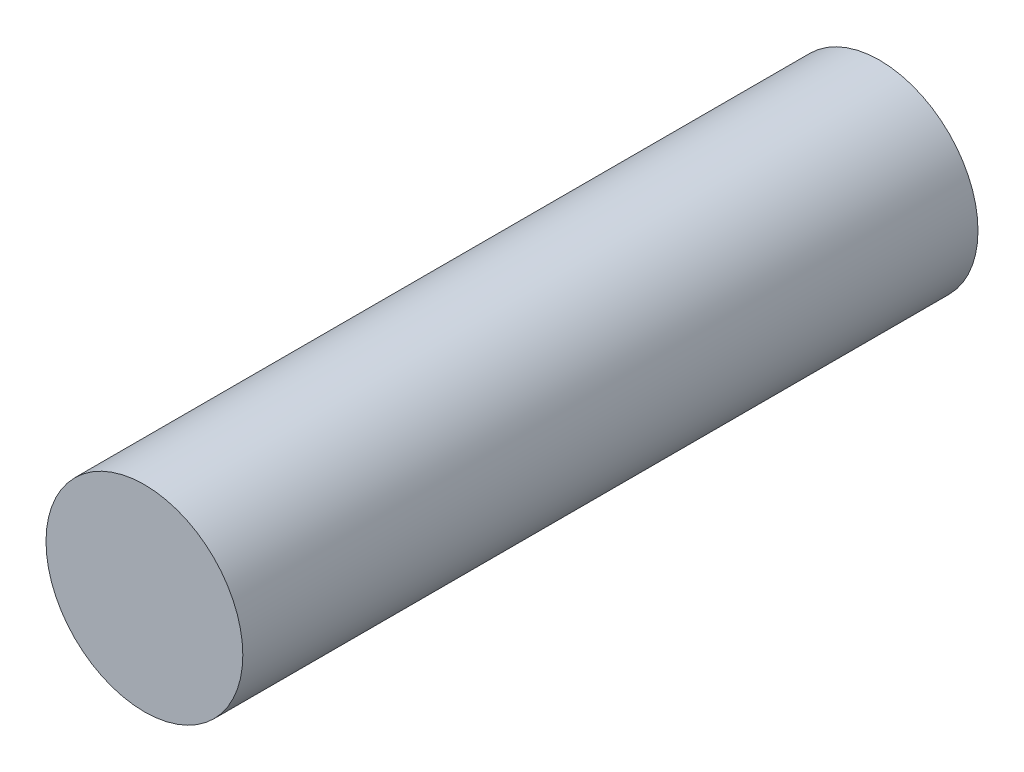
SolidWorks part; units mm, degrees
ref_plane "Front Plane" through (0, 0, 0) normal (0, 0, 1) x (1, 0, 0)
ref_plane "Top Plane" through (0, 0, 0) normal (0, 1, 0) x (1, 0, 0)
ref_plane "Right Plane" through (0, 0, 0) normal (1, 0, 0) x (0, 0, -1)
sketch "Sketch1" plane through (0, 0, 0) normal (0, 0, 1) x (1, 0, 0)
  circle A0 centre (0, 0) radius 8.5
  dimension "D1" = 17
extrude "Boss-Extrude1" add sketch "Sketch1" along normal blind 63.5
